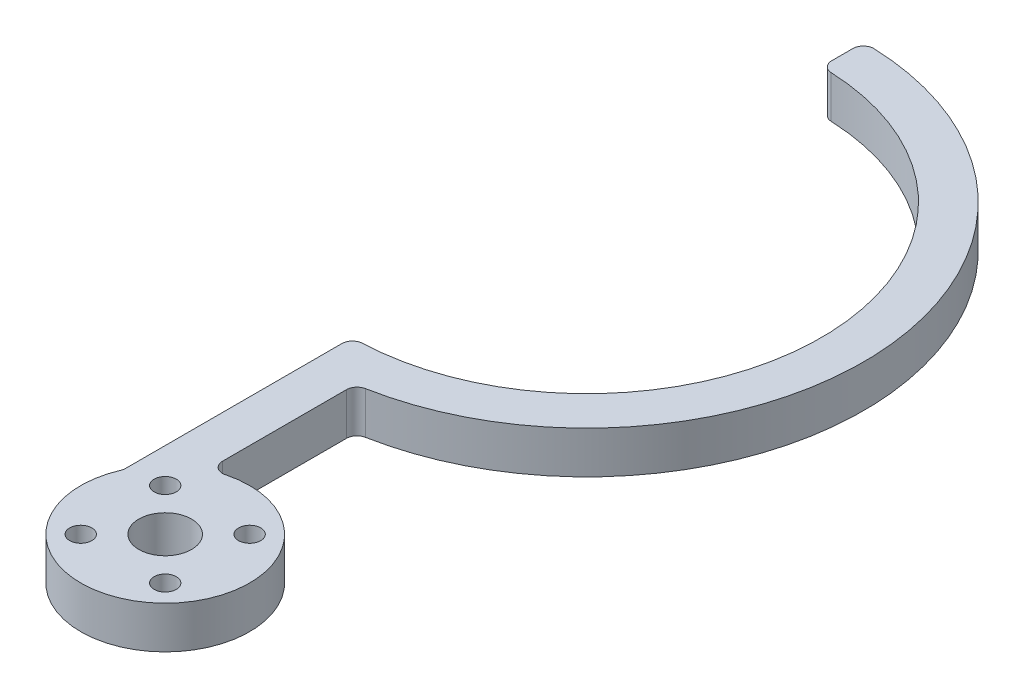
SolidWorks part; units mm, degrees
ref_plane "Front Plane" through (0, 0, 0) normal (0, 0, 1) x (1, 0, 0)
ref_plane "Top Plane" through (0, 0, 0) normal (0, 1, 0) x (1, 0, 0)
ref_plane "Right Plane" through (0, 0, 0) normal (1, 0, 0) x (0, 0, -1)
sketch "Sketch1" plane through (0, 0, 0) normal (0, 1, 0) x (1, 0, 0)
  line L0 (0, 52.45) -> (0, 44.45)
  line L3 (8, -51.8363) -> (8, -79.8363)
  line L7 (0, -44.45) -> (0, -87.7955)
  line L16 (6.5598, -86.4298) -> (22.5598, -86.4298) construction
  line L17 (6.5598, -86.4298) -> (6.5598, -102.4298) construction
  line L18 (6.5598, -102.4298) -> (22.5598, -102.4298) construction
  line L19 (22.5598, -86.4298) -> (22.5598, -102.4298) construction
  line L20 (6.5598, -86.4298) -> (22.5598, -102.4298) construction
  line L23 (6.5598, -102.4298) -> (22.5598, -86.4298) construction
  arc A0 (0, -44.45) -> (0, 44.45) centre (0, 0) ccw
  arc A1 (8, -51.8363) -> (0, 52.45) centre (0, 0) ccw
  arc A13 (0, -87.7955) -> (8, -79.8363) centre (14.5598, -94.4298) ccw
  circle A14 centre (22.5598, -86.4298) radius 2.1
  circle A15 centre (22.5598, -102.4298) radius 2.1
  circle A16 centre (6.5598, -102.4298) radius 2.1
  circle A17 centre (6.5598, -86.4298) radius 2.1
  circle A18 centre (14.5598, -94.4298) radius 5
  point P18 (25.8601, -73.4006)
  point P19 (27.5262, -71.9044)
  dimension "D1" = 88.9
  dimension "D4" = 16
  dimension "D7" = 4.2
  dimension "D8" = 10
  dimension "D2" = 8
  dimension "D3" = 8
  dimension "D6" = 16
  dimension "D5" = 28
extrude "Boss-Extrude2" add sketch "Sketch1" along normal blind 8
fillet "Fillet1" radius 2 6 edges at (0, 4, -44.45) (0, 4, -52.45) (8, 4, 51.8363) (8, 4, 79.8363) (0, 4, 87.7955) (0, 4, 44.45)
equation "\"innerSmall\"= 3.5in"
equation "\"thick\"= 8mm"
equation "\"D1@Sketch1\"=\"innerSmall\""
equation "\"D2@Sketch1\"=\"thick\""
equation "\"D3@Sketch1\"=\"thick\""
